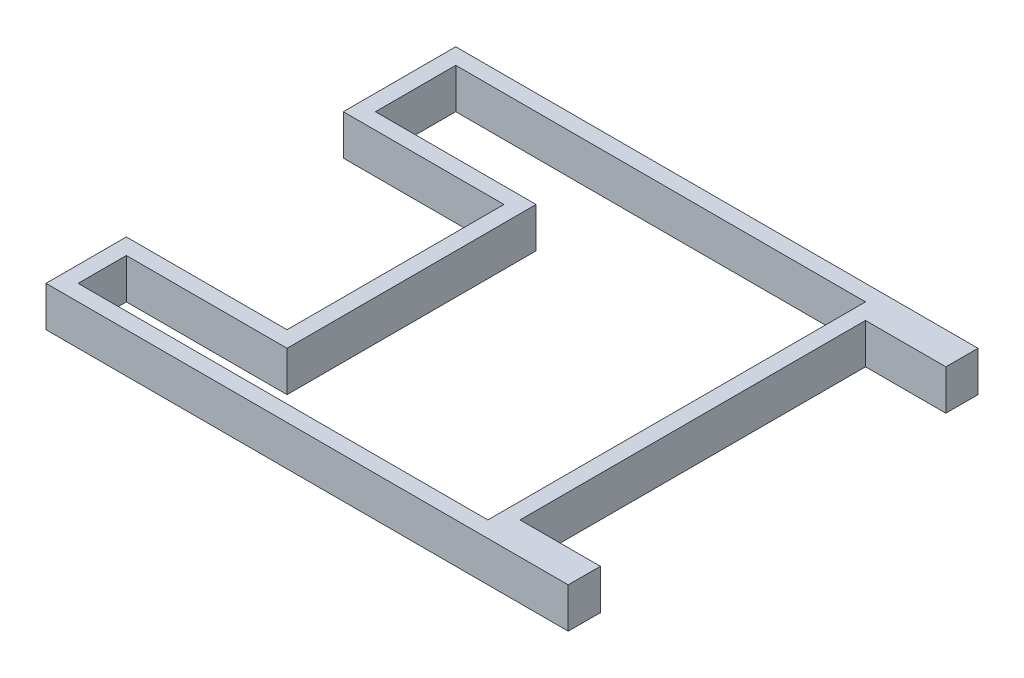
SolidWorks part; units mm, degrees
ref_plane "前视基准面" through (0, 0, 0) normal (0, 0, 1) x (1, 0, 0)
ref_plane "上视基准面" through (0, 0, 0) normal (0, 1, 0) x (1, 0, 0)
ref_plane "右视基准面" through (0, 0, 0) normal (1, 0, 0) x (0, 0, -1)
sketch "草图1" plane through (0, 0, 0) normal (0, 1, 0) x (1, 0, 0)
  line L0 (-44.7751, 7.1464) -> (-24.7751, 7.1464)
  line L1 (-44.7751, 21.1464) -> (20.2249, 21.1464) construction
  line L5 (-24.7751, 7.1464) -> (-24.7751, -19.8536)
  line L6 (-24.7751, -19.8536) -> (-44.7751, -19.8536)
  line L7 (-44.7751, -19.8536) -> (-44.7751, -29.8536)
  line L8 (-44.7751, -29.8536) -> (20.2249, -29.8536)
  line L9 (-44.7751, 21.1464) -> (20.2249, 21.1464)
  line L10 (20.2249, 21.1464) -> (20.2249, 17.1464)
  line L11 (20.2249, 17.1464) -> (10.2249, 17.1464)
  line L12 (10.2249, 17.1464) -> (10.2249, -25.8536)
  line L13 (10.2249, -25.8536) -> (20.2249, -25.8536)
  line L14 (20.2249, -25.8536) -> (20.2249, -29.8536)
  line L15 (-44.7751, 21.1464) -> (-44.7751, 7.1464)
  line L30 (-42.7751, 19.1464) -> (8.2249, 19.1464)
  line L31 (8.2249, 19.1464) -> (8.2249, -27.8536)
  line L32 (8.2249, -27.8536) -> (-42.7751, -27.8536)
  line L33 (-42.7751, -27.8536) -> (-42.7751, -21.8536)
  line L34 (-42.7751, -21.8536) -> (-22.7751, -21.8536)
  line L35 (-22.7751, -21.8536) -> (-22.7751, 9.1464)
  line L36 (-22.7751, 9.1464) -> (-42.7751, 9.1464)
  line L37 (-42.7751, 9.1464) -> (-42.7751, 19.1464)
  point P20 (-42.7751, -24.8536)
  dimension "D1" = 43
  dimension "D2" = 27
  dimension "D3" = 4
  dimension "D4" = 20
  dimension "D5" = 10
  dimension "D6" = 4
  dimension "D7" = 35
  dimension "D8" = 10
  dimension "D9" = 2
  dimension "D10" = 2
  dimension "D11" = 2
  dimension "D12" = 2
  dimension "D13" = 2
  dimension "D14" = 2
  dimension "D15" = 2
  dimension "D16" = 2
  dimension "D17" = 14
extrude "凸台-拉伸4" add sketch "草图1" along normal blind 5
